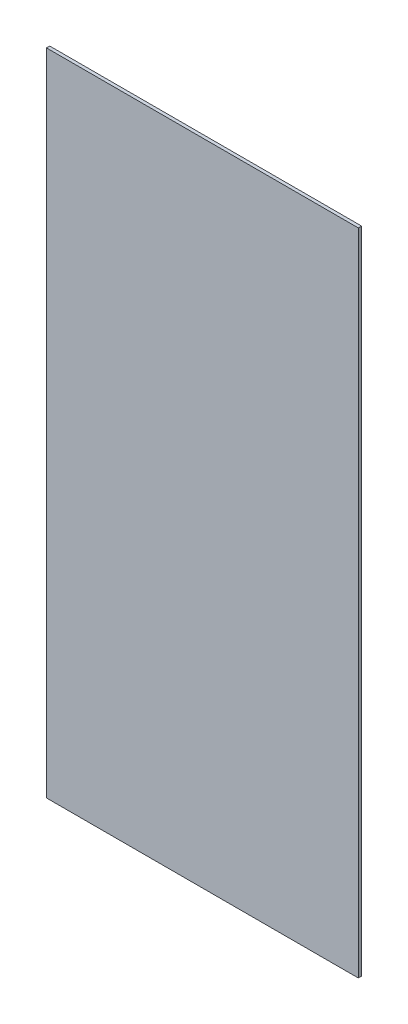
SolidWorks part; units mm, degrees
material "Гипс"
ref_plane "Спереди" through (0, 0, 0) normal (0, 0, 1) x (1, 0, 0)
ref_plane "Сверху" through (0, 0, 0) normal (0, 1, 0) x (1, 0, 0)
ref_plane "Справа" through (0, 0, 0) normal (1, 0, 0) x (0, 0, -1)
sketch "Эскиз1" plane through (0, 0, 0) normal (0, 0, 1) x (1, 0, 0)
  line L1 (0, 0) -> (-1200, 0)
  line L2 (0, 0) -> (0, 2500)
  line L3 (0, 2500) -> (-1200, 2500)
  line L4 (-1200, 0) -> (-1200, 2500)
  dimension "D1" = 1200
  dimension "D2" = 2500
extrude "Бобышка-Вытянуть1" add sketch "Эскиз1" against normal blind 12.5
sketch "Эскиз2" [suppressed] plane through (0, 0, -12.5) normal (0, 0, -1) x (-1, 0, 0)
  line L1 (600, 2090.75) -> (1200, 2090.75)
  line L2 (600, 2090.75) -> (600, 0)
  line L3 (600, 0) -> (1200, 0)
  line L4 (1200, 2090.75) -> (1200, 0)
extrude "Вырез-Вытянуть1" [suppressed] cut sketch "Эскиз2" against normal through all
sketch "Эскиз3" [suppressed] plane through (0, 0, 0) normal (0, 0, 1) x (1, 0, 0)
  line L0 (-1200, 2445) -> (-1200, 0) construction
  line L1 (-800, 1652.75) -> (-1200, 1652.75)
  line L2 (-800, 1652.75) -> (-800, 900)
  line L3 (-800, 900) -> (-1200, 900)
  line L4 (-1200, 1652.75) -> (-1200, 900)
  line L5 (-800, 900) -> (-1600, 900) construction
extrude "Вырез-Вытянуть2" [suppressed] cut sketch "Эскиз3" against normal through all
sketch "Эскиз4" [suppressed] plane through (0, 0, 0) normal (0, 0, 1) x (1, 0, 0)
  line L0 (0, 0) -> (0, 2445) construction
  line L1 (-50, 1700) -> (0, 1700)
  line L2 (-50, 1700) -> (-50, 900)
  line L3 (-50, 900) -> (0, 900)
  line L4 (0, 1700) -> (0, 900)
  line L5 (-50, 900) -> (1550, 900) construction
  line L7 (-50, 1700) -> (-50, 900) construction
extrude "Вырез-Вытянуть3" [suppressed] cut sketch "Эскиз4" against normal through all
sketch "Эскиз5" [suppressed] plane through (0, 0, 0) normal (0, 0, 1) x (1, 0, 0)
  line L0 (-1200, 2445) -> (-1200, 0) construction
  line L1 (0, 1700) -> (-1200, 1700)
  line L2 (0, 1700) -> (0, 900)
  line L3 (0, 900) -> (-1200, 900)
  line L4 (-1200, 1700) -> (-1200, 900)
  line L5 (-1250, 900) -> (350, 900) construction
extrude "Вырез-Вытянуть4" [suppressed] cut sketch "Эскиз5" against normal through all
sketch "Эскиз6" [suppressed] plane through (0, 0, 0) normal (0, 0, 1) x (1, 0, 0)
  line L1 (-700, 2091.5) -> (-1200, 2091.5)
  line L2 (-700, 2091.5) -> (-700, 0)
  line L3 (-700, 0) -> (-1200, 0)
  line L4 (-1200, 2091.5) -> (-1200, 0)
extrude "Вырез-Вытянуть5" [suppressed] cut sketch "Эскиз6" against normal through all
sketch "Эскиз7" [suppressed] plane through (0, 0, 0) normal (0, 0, 1) x (1, 0, 0)
  line L0 (0, 2500) -> (-1200, 2500) construction
  line L1 (0, 0) -> (-825, 0)
  line L2 (0, 0) -> (0, 2500)
  line L3 (0, 2500) -> (-825, 2500)
  line L4 (-825, 0) -> (-825, 2500)
  line L5 (-1200, 2500) -> (-1200, 0) construction
  dimension "D1" = 375
extrude "Вырез-Вытянуть6" [suppressed] cut sketch "Эскиз7" against normal through all
